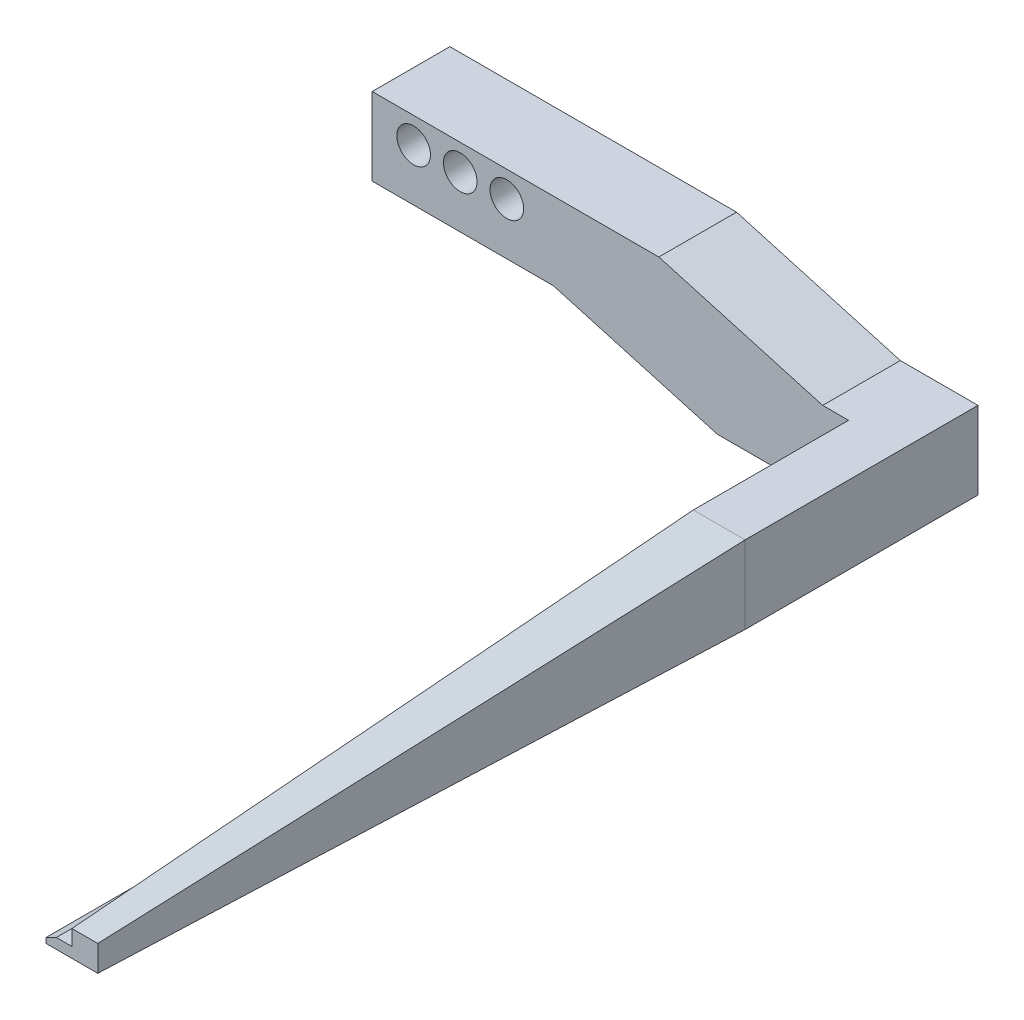
SolidWorks part; units mm, degrees
ref_plane "Ebene vorne" through (0, 0, 0) normal (0, 0, 1) x (1, 0, 0)
ref_plane "Ebene oben" through (0, 0, 0) normal (0, 1, 0) x (1, 0, 0)
ref_plane "Ebene rechts" through (0, 0, 0) normal (1, 0, 0) x (0, 0, -1)
sketch "Skizze1" plane through (0, 0, 0) normal (0, 0, 1) x (1, 0, 0)
  line L0 (10, 0) -> (65.3647, 0)
  line L1 (65.3647, 0) -> (97, -9)
  line L2 (97, -9) -> (112, -9)
  line L3 (112, -9) -> (112, -24)
  line L4 (112, -24) -> (76.6353, -24)
  line L5 (76.6353, -24) -> (45, -15)
  line L6 (45, -15) -> (10, -15)
  line L7 (10, -15) -> (10, 0)
  line L8 (0, 0) -> (0, 41.5317) construction
  line L9 (0, 0) -> (143.5408, 0) construction
  dimension "D1" = 10
  dimension "D2" = 112
  dimension "D3" = 15
  dimension "D4" = 15
  dimension "D5" = 24
  dimension "D6" = 15
  dimension "D7" = 20
  dimension "D8" = 35
extrude "Aufsatz-Linear austragen1" add sketch "Skizze1" along normal blind 15
sketch "Skizze2" plane through (0, 0, 15) normal (0, 0, 1) x (1, 0, 0)
  line L0 (112, -9) -> (112, -24)
  line L1 (112, -24) -> (97, -24)
  line L2 (76.6353, -24) -> (112, -24) construction
  line L3 (97, -24) -> (97, -23)
  line L4 (97, -23) -> (99, -22)
  line L5 (99, -22) -> (102, -22)
  line L6 (102, -22) -> (102, -9)
  line L7 (112, -9) -> (97, -9) construction
  line L8 (102, -9) -> (112, -9)
  dimension "D1" = 10
  dimension "D2" = 5
  dimension "D3" = 2
  dimension "D4" = 2
  dimension "D5" = 1
extrude "Aufsatz-Linear austragen2" add sketch "Skizze2" along normal blind 150
sketch "Skizze3" plane through (102, 0, 0) normal (-1, 0, 0) x (0, 0, 1)
  line L0 (165, -19) -> (45, -9)
  line L1 (165, -9) -> (165, -22) construction
  line L2 (165, -9) -> (15, -9) construction
  line L3 (45, -9) -> (165, -9)
  line L4 (165, -9) -> (165, -19)
  dimension "D1" = 120
  dimension "D2" = 10
extrude "Schnitt-Linear austragen1" cut sketch "Skizze3" against normal up to next
sketch "Skizze4" plane through (0, 0, 15) normal (0, 0, 1) x (1, 0, 0)
  line L0 (6.0648, -5) -> (44.6562, -5) construction
  line L1 (0, 0) -> (0, 17.7003) construction
  line L2 (65.3647, 0) -> (10, 0) construction
  circle A0 centre (36, -5) radius 1.7
  circle A1 centre (27, -5) radius 1.7
  circle A2 centre (18, -5) radius 1.7
  dimension "D1" = 3.4
  dimension "D5" = 5
  dimension "D2" = 9
  dimension "D3" = 9
  dimension "D4" = 18
extrude "Schnitt-Linear austragen2" cut sketch "Skizze4" against normal up to next
sketch "Skizze5" plane through (0, 0, 15) normal (0, 0, 1) x (1, 0, 0)
  circle A0 centre (18, -5) radius 3.25
  circle A1 centre (27, -5) radius 3.25
  circle A2 centre (36, -5) radius 3.25
  dimension "D1" = 6.5
extrude "Schnitt-Linear austragen3" cut sketch "Skizze5" against normal blind 9
sketch "Skizze6" plane through (0, -9, 0) normal (0, 1, 0) x (1, 0, 0)
  line L0 (112, -165) -> (107, -165)
  line L1 (112, -165) -> (102, -165) construction
  line L2 (107, -165) -> (112, -45)
  line L3 (112, -45) -> (112, -165)
  dimension "D1" = 5
extrude "Schnitt-Linear austragen4" cut sketch "Skizze6" against normal up to next
